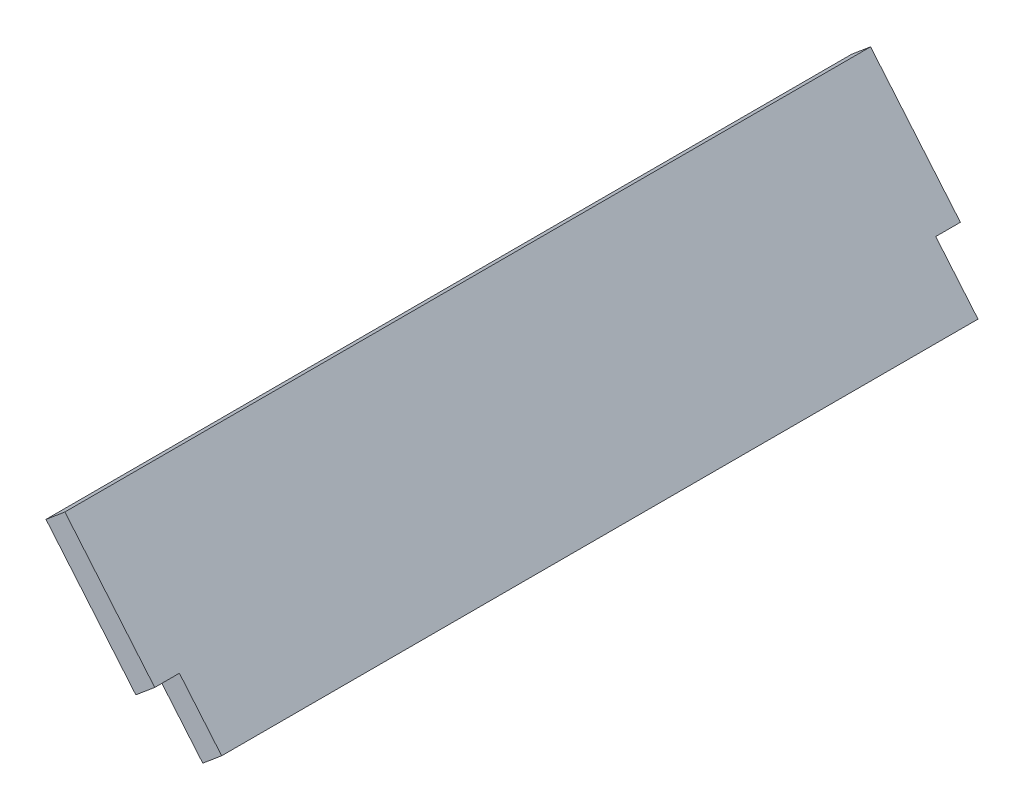
SolidWorks part; units mm, degrees
ref_plane "Front" through (0, 0, 0) normal (0, 0, 1) x (1, 0, 0)
ref_plane "Top" through (0, 0, 0) normal (0, 1, 0) x (1, 0, 0)
ref_plane "Right" through (0, 0, 0) normal (1, 0, 0) x (0, 0, -1)
sketch "Croquis1" plane through (0, 0, 0) normal (0, 0, 1) x (1, 0, 0)
  line L0 (0, 0) -> (16.0697, -19.1511)
  line L1 (0, 0) -> (-2.2981, -1.9284)
  line L2 (16.0697, -19.1511) -> (13.7716, -21.0795)
  line L3 (-2.2981, -1.9284) -> (13.7716, -21.0795)
  line L4 (13.7716, -21.0795) -> (30.7639, -21.0795) construction
  dimension "D1" = 25
  dimension "D2" = 3
  dimension "D3" = 40
extrude "Saliente-Extruir1" add sketch "Croquis1" along normal blind 92
sketch "Croquis3" plane through (-2.2981, -1.9284, 0) normal (-0.766, -0.6428, 0) x (0, 0, 1)
  line L0 (92, -25) -> (0, -25) construction
  line L1 (92, -17) -> (95, -17)
  line L2 (92, -17) -> (92, 0)
  line L3 (92, 0) -> (95, 0)
  line L4 (95, -17) -> (95, 0)
  line L5 (92, -17) -> (95, 0) construction
  line L6 (92, 0) -> (95, -17) construction
  line L7 (0, -17) -> (-3, -17)
  line L8 (0, -17) -> (0, 0)
  line L9 (0, 0) -> (-3, 0)
  line L10 (-3, -17) -> (-3, 0)
  line L11 (0, -17) -> (-3, 0) construction
  line L12 (0, 0) -> (-3, -17) construction
  point P4 (93.5, -8.5)
  point P10 (-1.5, -8.5)
  dimension "D1" = 3
  dimension "D2" = 8
  dimension "D3" = 8
  dimension "D4" = 3
  dimension "D5" = 92
extrude "Saliente-Extruir2" add sketch "Croquis3" against normal up to surface (3 mm away) up to face at (8.0348, -9.5756, 46)
